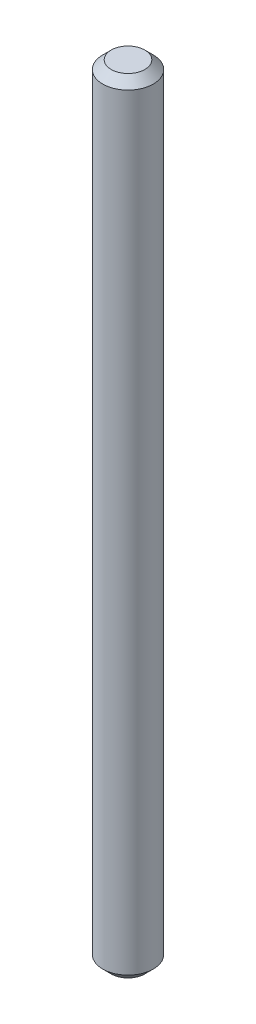
SolidWorks part; units mm, degrees
material "AISI 316 Stainless Steel Sheet (SS)"
ref_plane "Спереди" through (0, 0, 0) normal (0, 0, 1) x (1, 0, 0)
ref_plane "Сверху" through (0, 0, 0) normal (0, 1, 0) x (1, 0, 0)
ref_plane "Справа" through (0, 0, 0) normal (1, 0, 0) x (0, 0, -1)
sketch "Sketch1" plane through (0, 0, 0) normal (0, 0, 1) x (1, 0, 0)
  line L1 (0, 0) -> (3, 0)
  line L2 (0, 0) -> (0, 93)
  line L3 (0, 93) -> (3, 93)
  line L4 (3, 0) -> (3, 93)
  dimension "D1" = 93
  dimension "D2" = 3
revolve "Revolve1" add sketch "Sketch1" angle 360 about L2
chamfer "Chamfer1" distance 1 angle 45 2 edges at (0, 0, -3) (0, 93, -3)
